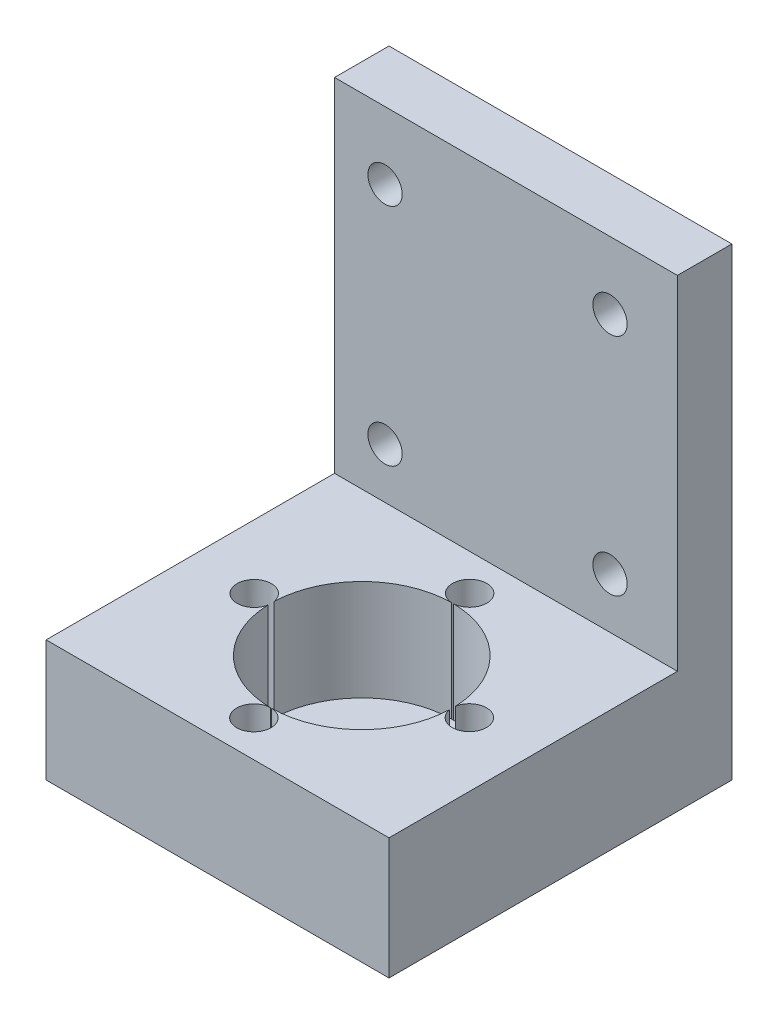
SolidWorks part; units mm, degrees
ref_plane "Front Plane" through (0, 0, 0) normal (0, 0, 1) x (1, 0, 0)
ref_plane "Top Plane" through (0, 0, 0) normal (0, 1, 0) x (1, 0, 0)
ref_plane "Right Plane" through (0, 0, 0) normal (1, 0, 0) x (0, 0, -1)
sketch "Sketch1" plane through (0, 0, 0) normal (0, 1, 0) x (1, 0, 0)
  line L1 (0, 0) -> (34, 0)
  line L2 (0, 0) -> (0, 34)
  line L3 (0, 34) -> (34, 34)
  line L4 (34, 0) -> (34, 34)
  dimension "D1" = 34
  dimension "D2" = 34
extrude "Boss-Extrude1" add sketch "Sketch1" along normal blind 12.04
sketch "Sketch2" plane through (0, 12.04, 0) normal (0, 1, 0) x (1, 0, 0)
  line L0 (34, 34) -> (0, 34) construction
  line L1 (0, 34) -> (34, 34)
  line L2 (0, 34) -> (0, 28.6)
  line L3 (0, 28.6) -> (34, 28.6)
  line L4 (34, 34) -> (34, 28.6)
  line L5 (34, 0) -> (34, 34) construction
  dimension "D1" = 5.4
extrude "Boss-Extrude2" add sketch "Sketch2" along normal blind 34
sketch "Sketch3" plane through (0, 12.04, 0) normal (0, 1, 0) x (1, 0, 0)
  line L0 (0, 14.3) -> (34.4972, 14.3) construction
  line L1 (0, 28.6) -> (0, 0) construction
  line L2 (17, 0) -> (17, 28.6) construction
  line L3 (0, 0) -> (34, 0) construction
  line L4 (0, 28.6) -> (34, 28.6) construction
  circle A4 centre (17, 14.3) radius 9
  dimension "D2" = 18
extrude "Cut-Extrude1" cut sketch "Sketch3" against normal blind 10
sketch "Sketch4" plane through (0, 12.04, 0) normal (0, 1, 0) x (1, 0, 0)
  line L0 (0, 14.3) -> (34, 14.3) construction
  line L1 (0, 28.6) -> (0, 0) construction
  line L2 (34, 0) -> (34, 28.6) construction
  line L3 (17, 0) -> (17, 28.6) construction
  line L4 (0, 0) -> (34, 0) construction
  line L5 (0, 28.6) -> (34, 28.6) construction
  circle A0 centre (6.3336, 14.3) radius 1.7
  circle A1 centre (27.6689, 14.3) radius 1.7
  circle A2 centre (17, 3.6009) radius 1.7
  circle A3 centre (17, 24.9974) radius 1.7
  dimension "D1" = 3.4
  dimension "D2" = 3.4
  dimension "D3" = 3.4
  dimension "D4" = 3.4
extrude "Cut-Extrude2" cut sketch "Sketch4" against normal through all
sketch "Sketch6" plane through (0, 2.04, 0) normal (0, 1, 0) x (1, 0, 0)
  circle A0 centre (17, 14.3) radius 3
  dimension "D1" = 6
extrude "Cut-Extrude3" cut sketch "Sketch6" against normal through all
sketch "Sketch7" plane through (0, 0, -28.6) normal (0, 0, 1) x (1, 0, 0)
  circle A0 centre (5.0067, 39.3571) radius 1.7
  circle A1 centre (27.3171, 39.3571) radius 1.7
  circle A2 centre (5.0067, 17.0467) radius 1.7
  circle A3 centre (27.3171, 17.0467) radius 1.7
  point P2 (27.3171, 17.0467)
  point P3 (5.0067, 17.0467)
  point P6 (5.0067, 39.3571)
  point P15 (27.3171, 39.3571)
  point P18 (5.0067, 17.0467)
  point P21 (27.3171, 17.0467)
  point P22 (5.0067, 39.3571)
  dimension "D1" = 3.4
extrude "Cut-Extrude4" cut sketch "Sketch7" against normal through all contours A2 | A0 | A1 | A3
equation "\"b\"= 34mm"
equation "\"l\"= 34mm"
equation "\"E\"= 2100"
equation "\"Sy\"= 45"
equation "\"defl\"= .30"
equation "\"SF\"= 3"
equation "\"M\"= 5400"
equation "\"h_1 defl\"= ( 6 * \"M\" * \"l\" ^ 2 / ( \"E\" * \"b\" * \"defl\" ) ) ^ ( 1 / 3 )"
equation "\"P\"= 300"
equation "\"h_2 stress\"= ( 6 * \"P\" * ( \"l\" / 4 ) * \"SF\" / ( \"Sy\" * \"b\" ) ) ^ ( 1 / 2 )"
